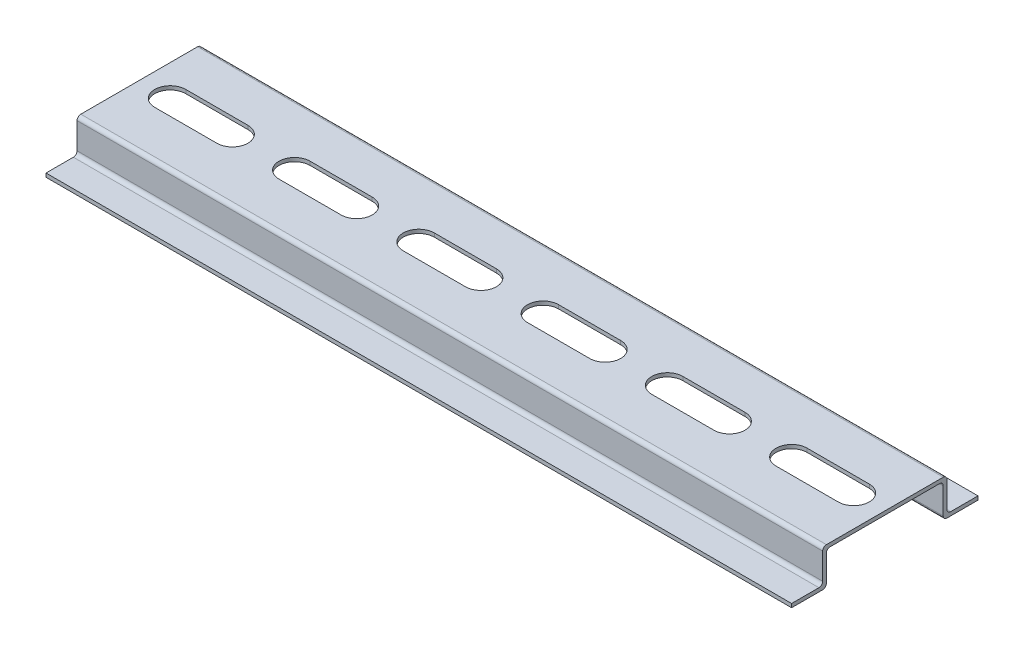
SolidWorks part; units mm, degrees
ref_plane "Front Plane" through (0, 0, 0) normal (0, 0, 1) x (1, 0, 0)
ref_plane "Top Plane" through (0, 0, 0) normal (0, 1, 0) x (1, 0, 0)
ref_plane "Right Plane" through (0, 0, 0) normal (1, 0, 0) x (0, 0, -1)
sketch "Sketch1" plane through (0, 0, 0) normal (1, 0, 0) x (0, 0, -1)
  line L0 (-21.2, 0) -> (-30, 0)
  line L1 (-20, -1.2) -> (-30, -1.2)
  line L2 (-20, 1.2) -> (-20, 9.6)
  line L3 (-18.8, 10.8) -> (18.8, 10.8)
  line L4 (20, 1.2) -> (20, 9.6)
  line L5 (-18.8, 0) -> (-18.8, 8.4)
  line L6 (-17.6, 9.6) -> (17.6, 9.6)
  line L7 (21.2, 0) -> (30, 0)
  line L8 (18.8, 0) -> (18.8, 8.4)
  line L9 (20, -1.2) -> (30, -1.2)
  line L10 (-30, -1.2) -> (-30, 0)
  line L11 (30, 0) -> (30, -1.2)
  line L12 (18.8, -1.2) -> (30, -1.2) construction
  line L13 (18.8, -1.2) -> (18.8, 9.6) construction
  line L14 (20, 0) -> (30, 0) construction
  line L15 (20, 0) -> (20, 10.8) construction
  line L16 (-20, 10.8) -> (20, 10.8) construction
  line L17 (-18.8, 9.6) -> (18.8, 9.6) construction
  line L18 (-20, 0) -> (-20, 10.8) construction
  line L19 (-18.8, -1.2) -> (-18.8, 9.6) construction
  line L20 (-20, 0) -> (-30, 0) construction
  line L21 (-18.8, -1.2) -> (-30, -1.2) construction
  arc A0 (20, -1.2) -> (18.8, 0) centre (20, 0) cw
  arc A1 (21.2, 0) -> (20, 1.2) centre (21.2, 1.2) cw
  arc A2 (20, 9.6) -> (18.8, 10.8) centre (18.8, 9.6) ccw
  arc A3 (18.8, 8.4) -> (17.6, 9.6) centre (17.6, 8.4) ccw
  arc A4 (-18.8, 10.8) -> (-20, 9.6) centre (-18.8, 9.6) ccw
  arc A5 (-17.6, 9.6) -> (-18.8, 8.4) centre (-17.6, 8.4) ccw
  arc A6 (-20, 1.2) -> (-21.2, 0) centre (-21.2, 1.2) cw
  arc A7 (-18.8, 0) -> (-20, -1.2) centre (-20, 0) cw
  point P0 (0, 0)
  point P20 (20, 0)
  dimension "D7" = 1.2
  dimension "D2" = 60
  dimension "D3" = 30
  dimension "D5" = 12
  dimension "D6" = 1.2
extrude "Boss-Extrude1" add sketch "Sketch1" against normal blind 240
sketch "Sketch2" plane through (0, 10.8, 0) normal (0, 1, 0) x (1, 0, 0)
  line L0 (-230, 0) -> (-210, 0) construction
  line L1 (-230, 5) -> (-210, 5)
  line L2 (-230, -5) -> (-210, -5)
  line L3 (-240, 18.8) -> (-240, -18.8) construction
  line L4 (-190, 0) -> (-170, 0) construction
  line L5 (-190, 5) -> (-170, 5)
  line L6 (-190, -5) -> (-170, -5)
  line L7 (-150, 0) -> (-130, 0) construction
  line L8 (-150, 5) -> (-130, 5)
  line L9 (-150, -5) -> (-130, -5)
  line L10 (-110, 0) -> (-90, 0) construction
  line L11 (-110, 5) -> (-90, 5)
  line L12 (-110, -5) -> (-90, -5)
  line L13 (-70, 0) -> (-50, 0) construction
  line L14 (-70, 5) -> (-50, 5)
  line L15 (-70, -5) -> (-50, -5)
  line L16 (-30, 0) -> (-10, 0) construction
  line L17 (-30, 5) -> (-10, 5)
  line L18 (-30, -5) -> (-10, -5)
  arc A0 (-230, 5) -> (-230, -5) centre (-230, 0) ccw
  arc A1 (-210, -5) -> (-210, 5) centre (-210, 0) ccw
  arc A2 (-190, 5) -> (-190, -5) centre (-190, 0) ccw
  arc A3 (-170, -5) -> (-170, 5) centre (-170, 0) ccw
  arc A4 (-150, 5) -> (-150, -5) centre (-150, 0) ccw
  arc A5 (-130, -5) -> (-130, 5) centre (-130, 0) ccw
  arc A6 (-110, 5) -> (-110, -5) centre (-110, 0) ccw
  arc A7 (-90, -5) -> (-90, 5) centre (-90, 0) ccw
  arc A8 (-70, 5) -> (-70, -5) centre (-70, 0) ccw
  arc A9 (-50, -5) -> (-50, 5) centre (-50, 0) ccw
  arc A10 (-30, 5) -> (-30, -5) centre (-30, 0) ccw
  arc A11 (-10, -5) -> (-10, 5) centre (-10, 0) ccw
  point P2 (-220, 0)
  point P14 (-180, 0)
  point P21 (-140, 0)
  point P28 (-100, 0)
  point P35 (-60, 0)
  point P42 (-20, 0)
  dimension "D1" = 10
  dimension "D2" = 20
  dimension "D3" = 10
  dimension "D4" = 6
extrude "Cut-Extrude1" cut sketch "Sketch2" against normal through all
